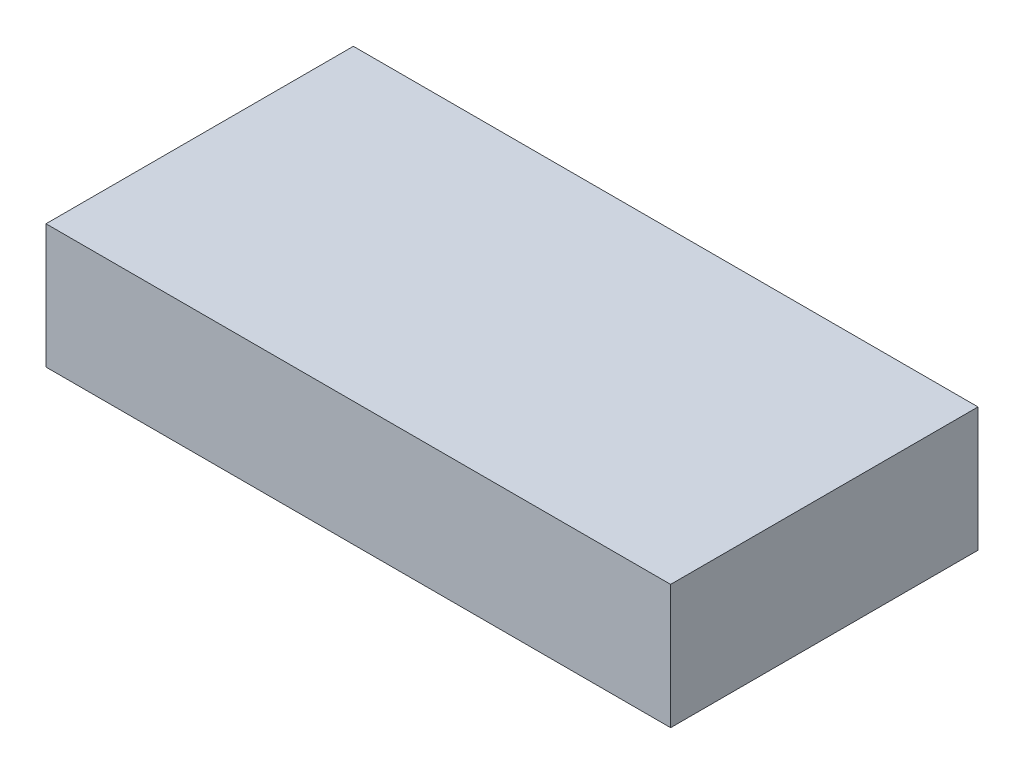
SolidWorks part; units mm, degrees
ref_plane "Front Plane" through (0, 0, 0) normal (0, 0, 1) x (1, 0, 0)
ref_plane "Top Plane" through (0, 0, 0) normal (0, 1, 0) x (1, 0, 0)
ref_plane "Right Plane" through (0, 0, 0) normal (1, 0, 0) x (0, 0, -1)
sketch "Sketch1" plane through (0, 0, 0) normal (0, 1, 0) x (1, 0, 0)
  line L1 (-7.925, 3.9) -> (7.925, 3.9)
  line L2 (-7.925, 3.9) -> (-7.925, -3.9)
  line L3 (-7.925, -3.9) -> (7.925, -3.9)
  line L4 (7.925, 3.9) -> (7.925, -3.9)
  line L5 (-7.925, 3.9) -> (7.925, -3.9) construction
  line L6 (-7.925, -3.9) -> (7.925, 3.9) construction
  point P0 (0, 0)
  dimension "D1" = 15.85
  dimension "D2" = 7.8
extrude "Boss-Extrude1" add sketch "Sketch1" against normal blind 3.15
shell "Shell1" thickness 1.5
